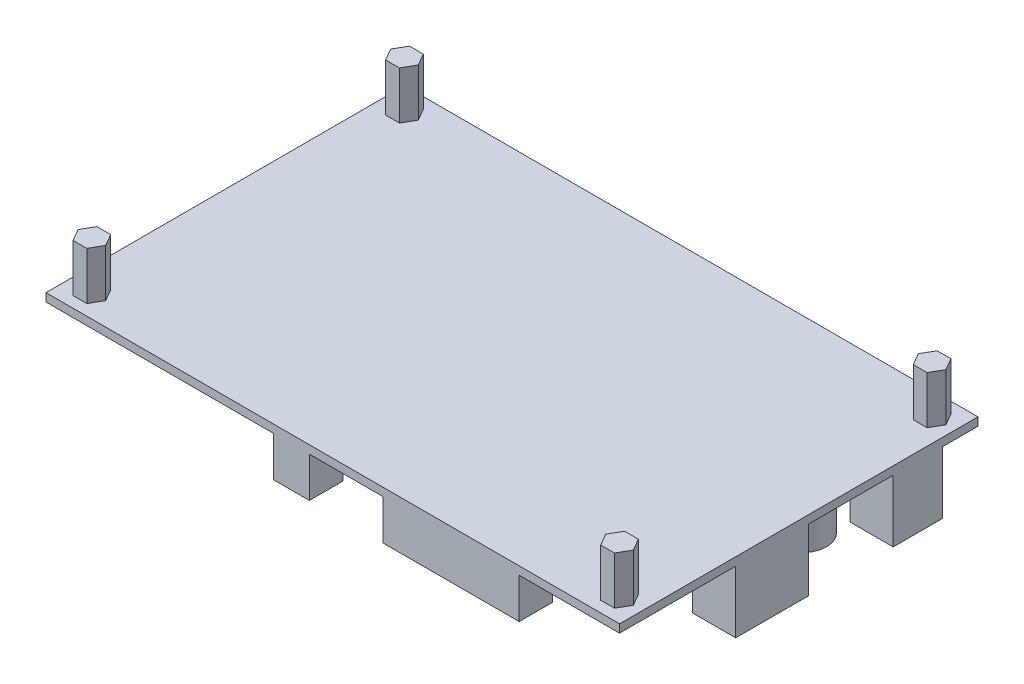
SolidWorks part; units mm, degrees
ref_plane "Спереди" through (0, 0, 0) normal (0, 0, 1) x (1, 0, 0)
ref_plane "Сверху" through (0, 0, 0) normal (0, 1, 0) x (1, 0, 0)
ref_plane "Справа" through (0, 0, 0) normal (1, 0, 0) x (0, 0, -1)
sketch "Эскиз1" plane through (0, 0, 0) normal (0, 1, 0) x (1, 0, 0)
  line L0 (0, 37.5) -> (0, -60.3581) construction
  line L1 (-60, 37.5) -> (60, 37.5)
  line L2 (-60, 37.5) -> (-60, -37.5)
  line L3 (-60, -37.5) -> (60, -37.5)
  line L4 (60, 37.5) -> (60, -37.5)
  line L5 (-60, 37.5) -> (60, -37.5) construction
  line L6 (-60, -37.5) -> (60, 37.5) construction
  line L7 (-60, 0) -> (151.0258, 0) construction
  point P0 (0, 0)
  dimension "D1" = 75
  dimension "D2" = 120
extrude "Бобышка-Вытянуть1" add sketch "Эскиз1" along normal blind 1.7
sketch "Эскиз2" plane through (0, 1.7, 0) normal (0, 1, 0) x (1, 0, 0)
  line L0 (-60, -37.5) -> (60, -37.5) construction
  line L1 (-53.7566, -30.2) -> (-56.6434, -30.2)
  line L2 (-56.6434, -30.2) -> (-58.0868, -32.7)
  line L3 (-58.0868, -32.7) -> (-56.6434, -35.2)
  line L4 (-56.6434, -35.2) -> (-53.7566, -35.2)
  line L5 (-53.7566, -35.2) -> (-52.3132, -32.7)
  line L6 (-52.3132, -32.7) -> (-53.7566, -30.2)
  line L7 (-60, 37.5) -> (-60, -37.5) construction
  line L8 (0, -37.5) -> (0, 47.1108) construction
  line L9 (-60, 0) -> (122.3197, 0) construction
  line L10 (56.6434, -35.2) -> (53.7566, -35.2)
  line L11 (58.0868, -32.7) -> (56.6434, -35.2)
  line L12 (60, 37.5) -> (-60, 37.5)
  line L13 (60, -37.5) -> (60, 37.5)
  line L14 (-60, -37.5) -> (60, -37.5)
  line L15 (-60, 37.5) -> (-60, -37.5)
  line L16 (60, 37.5) -> (-60, 37.5)
  line L17 (60, -37.5) -> (60, 37.5)
  line L18 (-60, -37.5) -> (60, -37.5)
  line L19 (-60, 37.5) -> (-60, -37.5)
  line L20 (56.6434, -30.2) -> (58.0868, -32.7)
  line L21 (53.7566, -30.2) -> (56.6434, -30.2)
  line L22 (52.3132, -32.7) -> (53.7566, -30.2)
  line L23 (53.7566, -35.2) -> (52.3132, -32.7)
  line L24 (52.3132, 32.7) -> (53.7566, 30.2)
  line L25 (53.7566, 35.2) -> (52.3132, 32.7)
  line L26 (56.6434, 35.2) -> (53.7566, 35.2)
  line L27 (58.0868, 32.7) -> (56.6434, 35.2)
  line L28 (56.6434, 30.2) -> (58.0868, 32.7)
  line L29 (53.7566, 30.2) -> (56.6434, 30.2)
  line L30 (-58.0868, 32.7) -> (-56.6434, 35.2)
  line L31 (-56.6434, 35.2) -> (-53.7566, 35.2)
  line L32 (-53.7566, 35.2) -> (-52.3132, 32.7)
  line L33 (-52.3132, 32.7) -> (-53.7566, 30.2)
  line L34 (-53.7566, 30.2) -> (-56.6434, 30.2)
  line L35 (-56.6434, 30.2) -> (-58.0868, 32.7)
  circle A0 centre (-55.2, -32.7) radius 2.5 construction
  dimension "D1" = 4.8
  dimension "D2" = 4.8
  dimension "D3" = 5
  dimension "D4" = 0
extrude "Бобышка-Вытянуть2" add sketch "Эскиз2" along normal blind 10 contours L30 L31 L32 L33 L34 L35 | L1 L2 L3 L4 L5 L6 | L10 L23 L22 L21 L20 L11 | L24 L29 L28 L27 L26 L25
sketch "Эскиз3" plane through (0, 0, 0) normal (0, -1, 0) x (1, 0, 0)
  line L0 (-60, 37.5) -> (60, 37.5) construction
  line L1 (-8.65, 37.5) -> (-4.9, 37.5)
  line L2 (-8.65, 37.5) -> (-8.65, 30.5)
  line L3 (-8.65, 30.5) -> (-4.9, 30.5)
  line L4 (-4.9, 37.5) -> (-4.9, 30.5)
  line L5 (-60, -37.5) -> (-60, 37.5) construction
  dimension "D1" = 55.1
  dimension "D2" = 3.75
  dimension "D3" = 7
extrude "Бобышка-Вытянуть3" add sketch "Эскиз3" along normal blind 8.4
mirror "Зеркальное отражение2" about plane through (-8.65, -8.4, 37.5) normal (1, 0, 0) of "Бобышка-Вытянуть3"
sketch "Эскиз4" plane through (0, 0, 0) normal (0, -1, 0) x (1, 0, 0)
  line L0 (-4.9, 37.5) -> (60, 37.5) construction
  line L1 (10.5, 37.5) -> (39, 37.5)
  line L2 (10.5, 37.5) -> (10.5, 30.5)
  line L3 (10.5, 30.5) -> (39, 30.5)
  line L4 (39, 37.5) -> (39, 30.5)
  line L5 (60, 37.5) -> (60, -37.5) construction
  point P8 (39, 34)
  dimension "D1" = 49.5
  dimension "D2" = 7
  dimension "D3" = 28.5
extrude "Бобышка-Вытянуть4" add sketch "Эскиз4" along normal blind 8.4
sketch "Эскиз5" plane through (0, 0, 0) normal (0, -1, 0) x (1, 0, 0)
  line L0 (60, 37.5) -> (60, -37.5) construction
  line L1 (60, 13.2) -> (51, 13.2)
  line L2 (60, 13.2) -> (60, -2)
  line L3 (60, -2) -> (51, -2)
  line L4 (51, 13.2) -> (51, -2)
  line L5 (39, 37.5) -> (60, 37.5) construction
  dimension "D1" = 39.5
  dimension "D2" = 15.2
  dimension "D3" = 9
extrude "Бобышка-Вытянуть5" add sketch "Эскиз5" along normal blind 13
sketch "Эскиз6" plane through (0, 0, 0) normal (0, -1, 0) x (1, 0, 0)
  line L0 (60, -2) -> (60, -37.5) construction
  line L1 (60, -19.75) -> (51, -19.75)
  line L2 (60, -19.75) -> (60, -30.05)
  line L3 (60, -30.05) -> (51, -30.05)
  line L4 (51, -19.75) -> (51, -30.05)
  dimension "D1" = 10.3
  dimension "D2" = 9
extrude "Бобышка-Вытянуть6" add sketch "Эскиз6" along normal blind 13
sketch "Эскиз7" plane through (0, 0, 0) normal (0, -1, 0) x (1, 0, 0)
  line L0 (60, -2) -> (60, -19.75) construction
  line L1 (60, -37.5) -> (-60, -37.5) construction
  circle A0 centre (44.6, -16.1) radius 5.1
  dimension "D1" = 10.2
  dimension "D2" = 15.4
  dimension "D3" = 21.4
extrude "Бобышка-Вытянуть7" add sketch "Эскиз7" along normal blind 16.3
sketch "Эскиз8" plane through (0, 0, 0) normal (0, -1, 0) x (1, 0, 0)
  line L0 (60, -37.5) -> (-60, -37.5) construction
  line L1 (11.7, -6.9) -> (8.7, -6.9)
  line L2 (11.7, -6.9) -> (11.7, -8.9)
  line L3 (11.7, -8.9) -> (8.7, -8.9)
  line L4 (8.7, -6.9) -> (8.7, -8.9)
  line L5 (-60, -37.5) -> (-60, 37.5) construction
  dimension "D1" = 3
  dimension "D2" = 2
  dimension "D3" = 30.6
  dimension "D4" = 71.7
extrude "Бобышка-Вытянуть8" add sketch "Эскиз8" along normal blind 3
sketch "Эскиз9" plane through (0, -3, 0) normal (0, -1, 0) x (1, 0, 0)
  line L0 (10.3356, -8.9) -> (10.3356, -0.8195) construction
  line L1 (10.8356, -7.3871) -> (9.8356, -7.3871)
  line L2 (10.8356, -7.3871) -> (10.8356, -8.3871)
  line L3 (10.8356, -8.3871) -> (9.8356, -8.3871)
  line L4 (9.8356, -7.3871) -> (9.8356, -8.3871)
  line L5 (10.8356, -7.3871) -> (9.8356, -8.3871) construction
  line L6 (10.8356, -8.3871) -> (9.8356, -7.3871) construction
  line L8 (11.7, -7.8871) -> (4.7379, -7.8871) construction
  line L10 (8.7, -6.9) -> (8.7, -8.9) construction
  point P0 (10.3356, -7.8871)
  point P7 (8.7, -7.9)
  point P8 (8.7, -7.9)
  dimension "D1" = 1
  dimension "D2" = 1
extrude "Бобышка-Вытянуть9" add sketch "Эскиз9" along normal blind 8
pattern_linear "Линейный массив2" count 13 spacing 4.1833 along (-1, 0, 0) of "Бобышка-Вытянуть9", "Бобышка-Вытянуть8"
pattern_linear "Линейный массив3" count 2 spacing 2.5 along (0, 0, -1) of "Линейный массив2", "Бобышка-Вытянуть8", "Бобышка-Вытянуть9"
